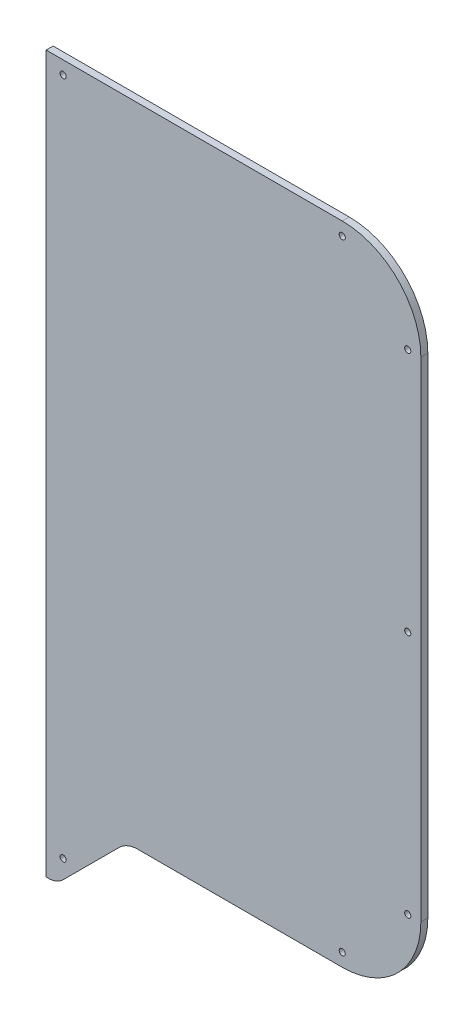
SolidWorks part; units mm, degrees
ref_plane "Front Plane" through (0, 0, 0) normal (0, 0, 1) x (1, 0, 0)
ref_plane "Top Plane" through (0, 0, 0) normal (0, 1, 0) x (1, 0, 0)
ref_plane "Right Plane" through (0, 0, 0) normal (1, 0, 0) x (0, 0, -1)
sketch "Sketch1" plane through (0, 0, 0) normal (0, 0, 1) x (1, 0, 0)
  line L0 (2193.8217, 382.11) -> (2024.3217, 382.11) construction
  line L1 (2231.3217, 64.61) -> (2231.3217, 344.61) construction
  line L2 (2076.7574, 27.11) -> (2193.8217, 27.11) construction
  line L3 (2028.7456, -11.5724) -> (2060.8499, 20.5223) construction
  line L18 (2024.3217, -20.39) -> (2025.5641, -20.39)
  line L19 (2024.3217, -5.39) -> (2024.3217, -101.39) construction
  line L22 (2034.9267, -15.9982) -> (2066.1524, 15.2182)
  line L23 (2193.8217, 389.61) -> (2024.3217, 389.61)
  line L24 (2238.8217, 64.61) -> (2238.8217, 344.61)
  line L25 (2076.7574, 19.61) -> (2193.8217, 19.61)
  line L26 (2034.0481, -16.8765) -> (2066.1524, 15.2182)
  line L27 (2193.8217, 389.61) -> (2024.3217, 389.61)
  line L28 (2238.8217, 64.61) -> (2238.8217, 344.61)
  line L29 (2076.7574, 19.61) -> (2193.8217, 19.61)
  line L35 (2024.3217, 389.61) -> (2024.3217, -20.39)
  arc A0 (2034.0481, -16.8765) -> (2025.5641, -20.39) centre (2025.5641, -8.39) cw
  arc A1 (2231.3217, 344.61) -> (2193.8217, 382.11) centre (2193.8217, 344.61) ccw construction
  arc A2 (2193.8217, 27.11) -> (2231.3217, 64.61) centre (2193.8217, 64.61) ccw construction
  arc A3 (2076.7574, 27.11) -> (2060.8499, 20.5223) centre (2076.7574, 4.61) ccw construction
  arc A4 (2028.7456, -11.5724) -> (2025.5641, -12.89) centre (2025.5641, -8.39) cw construction
  circle A5 centre (2034.0481, -6.2715) radius 1.75
  circle A7 centre (2193.8217, 27.11) radius 1.75
  circle A8 centre (2231.3217, 64.61) radius 1.75
  circle A9 centre (2231.3217, 204.61) radius 1.75
  circle A10 centre (2231.3217, 344.61) radius 1.75
  circle A11 centre (2193.8217, 382.11) radius 1.75
  circle A13 centre (2034.0481, 382.11) radius 1.75
  arc A15 (2076.7574, 19.61) -> (2066.1524, 15.2182) centre (2076.7574, 4.61) ccw
  arc A16 (2238.8217, 344.61) -> (2193.8217, 389.61) centre (2193.8217, 344.61) ccw
  arc A17 (2193.8217, 19.61) -> (2238.8217, 64.61) centre (2193.8217, 64.61) ccw
  arc A18 (2076.7574, 19.61) -> (2066.1524, 15.2182) centre (2076.7574, 4.61) ccw
  arc A19 (2238.8217, 344.61) -> (2193.8217, 389.61) centre (2193.8217, 344.61) ccw
  arc A20 (2193.8217, 19.61) -> (2238.8217, 64.61) centre (2193.8217, 64.61) ccw
  dimension "D1" = 15
  dimension "D2" = 12
extrude "Boss-Extrude1" add sketch "Sketch1" along normal blind 4
